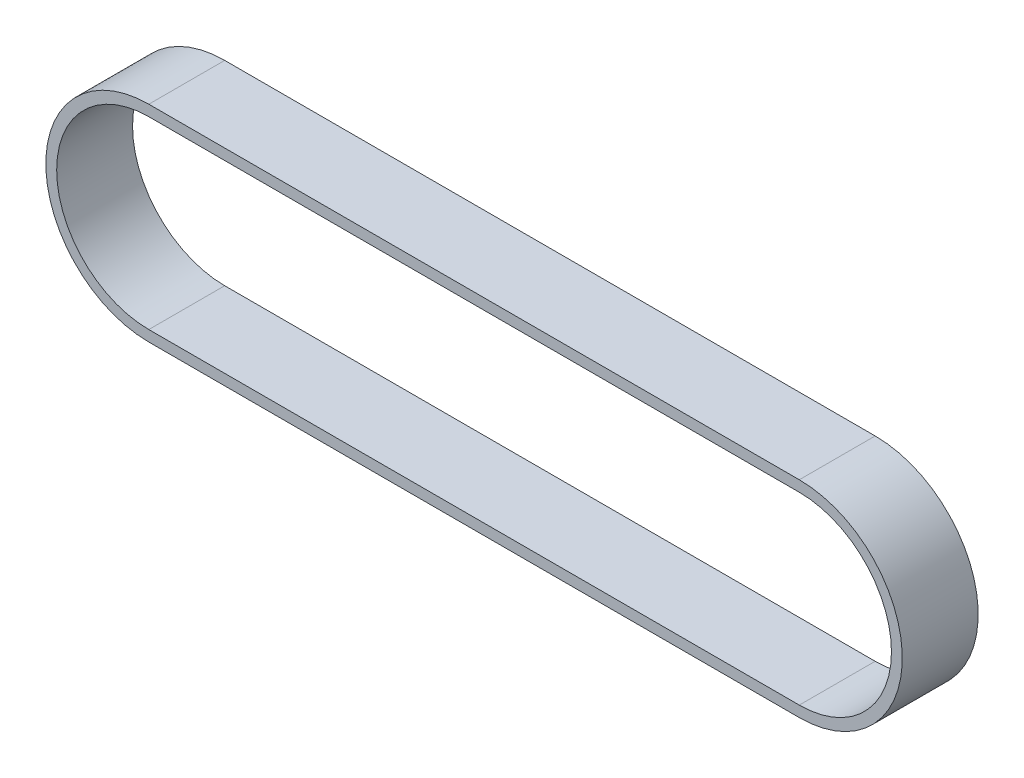
SolidWorks part; units mm, degrees
ref_plane "前视基准面" through (0, 0, 0) normal (0, 0, 1) x (1, 0, 0)
ref_plane "上视基准面" through (0, 0, 0) normal (0, 1, 0) x (1, 0, 0)
ref_plane "右视基准面" through (0, 0, 0) normal (1, 0, 0) x (0, 0, -1)
other "Configuration Table"
sketch "草图1" plane through (0, 0, 0) normal (0, 0, 1) x (1, 0, 0)
  line L0 (-46.0545, 0) -> (73.9455, 0) construction
  line L1 (-46.0545, 17) -> (73.9455, 17)
  line L2 (-46.0545, -17) -> (73.9455, -17)
  arc A0 (-46.0545, 17) -> (-46.0545, -17) centre (-46.0545, 0) ccw
  arc A1 (73.9455, -17) -> (73.9455, 17) centre (73.9455, 0) ccw
  point P3 (13.9455, 0)
  dimension "D1" = 17
  dimension "D2" = 120
extrude "拉伸-薄壁1" add sketch "草图1" along normal mid plane 14 thin thin type one direction wall 2
